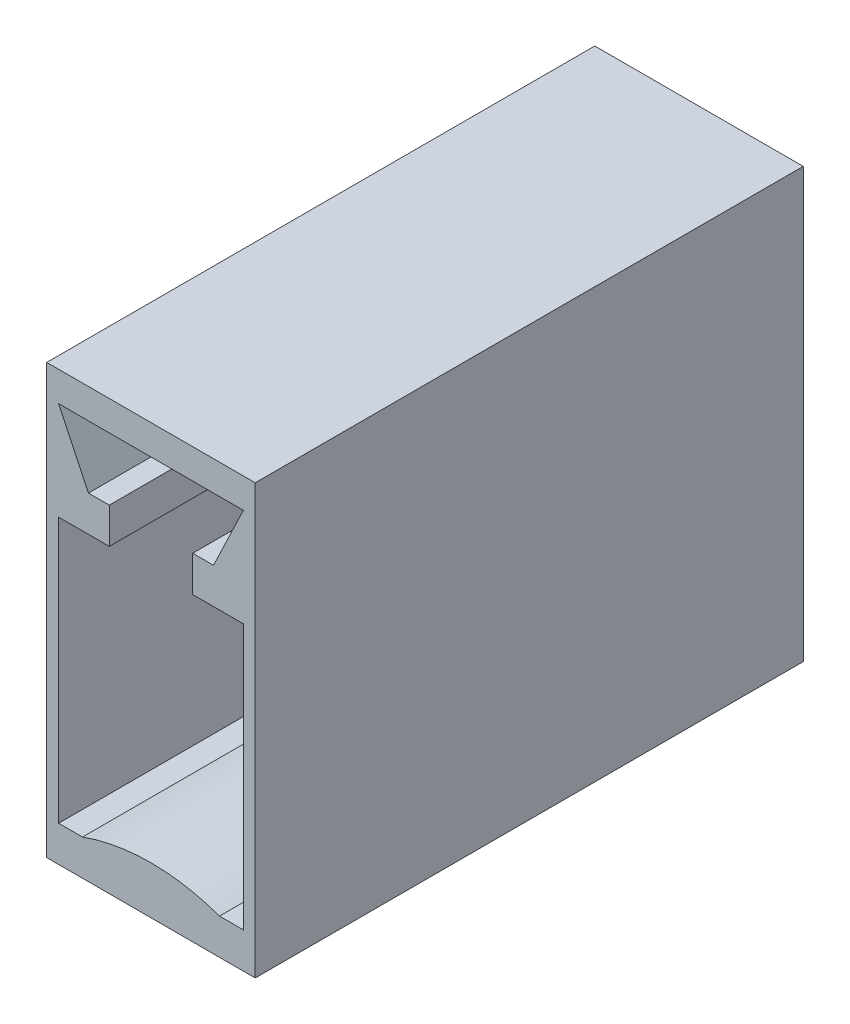
SolidWorks part; units mm, degrees
ref_plane "Спереди" through (0, 0, 0) normal (0, 0, 1) x (1, 0, 0)
ref_plane "Сверху" through (0, 0, 0) normal (0, 1, 0) x (1, 0, 0)
ref_plane "Справа" through (0, 0, 0) normal (1, 0, 0) x (0, 0, -1)
ref_plane "Плоскость1" through (0, -3.6, 0) normal (0, -1, 0) x (1, 0, 0)
sketch "Эскиз1" plane through (0, -3.6, 0) normal (0, -1, 0) x (1, 0, 0)
  line L0 (-3.5, 4.6) -> (-3.5, -4.6)
  line L1 (-3.5, -4.6) -> (0, -4.6)
  line L2 (0, -4.6) -> (0, 4.6)
  line L3 (0, 4.6) -> (-3.5, 4.6)
  line L4 (0, -3.9231) -> (0, 3.5325) construction
  dimension "D1" = 3.5
  dimension "D2" = 9.2
  dimension "D3" = 3.5
extrude "Бобышка-Вытянуть1" add sketch "Эскиз1" against normal blind 7.2
sketch "Эскиз2" plane through (0, -3.6, 0) normal (0, -1, 0) x (1, 0, 0)
  line L0 (-3.125, -1.55) -> (-3.125, -4.6)
  line L1 (-3.125, -4.6) -> (-0.375, -4.6)
  line L2 (-0.375, -4.6) -> (-0.375, -1.55)
  line L3 (-0.375, -1.55) -> (-3.125, -1.55)
extrude "Вырез-Вытянуть1" cut sketch "Эскиз2" against normal blind 0.4
sketch "Эскиз5" plane through (0, 0, -4.6) normal (0, 0, -1) x (-1, 0, 0)
  line L0 (0.375, 0.6) -> (0.375, -3.2)
  line L1 (0.375, -3.2) -> (3.125, -3.2)
  line L2 (3.125, -3.2) -> (3.125, 0.6)
  line L3 (3.125, 0.6) -> (0.375, 0.6)
extrude "Вырез-Вытянуть4" cut sketch "Эскиз5" against normal blind 0.4
ref_plane "Плоскость2" through (0, 0, -2.3) normal (0, 0, -1) x (-1, 0, 0)
sketch "Эскиз7" plane through (0, 0, -2.3) normal (0, 0, -1) x (-1, 0, 0)
  line L0 (3.3, -1.1) -> (3.3, -0.1)
  line L1 (3.3, -0.1) -> (2.9, -0.1)
  line L2 (2.9, -0.1) -> (2.9, 1.1)
  line L3 (2.9, 1.1) -> (0.6, 1.1)
  line L4 (0.6, 1.1) -> (0.6, -0.1)
  line L5 (0.6, -0.1) -> (0.2, -0.1)
  line L6 (0.2, -0.1) -> (0.2, -1.1)
  line L7 (0.2, -1.1) -> (0.6, -1.1)
  line L8 (0.6, -1.1) -> (0.6, -3)
  line L9 (2.9, -3) -> (2.9, -1.1)
  line L10 (2.9, -1.1) -> (3.3, -1.1)
  arc A0 (0.6, -3) -> (2.9, -3) centre (1.75, -6.2062) cw
extrude "Вырез-Вытянуть6" cut sketch "Эскиз7" against normal up to next
ref_plane "Плоскость3" through (0, 0, -1) normal (0, 0, 1) x (1, 0, 0)
sketch "Эскиз9" plane through (0, 0, -1) normal (0, 0, 1) x (1, 0, 0)
  circle A0 centre (-1.75, -0.6) radius 0.9
extrude "Бобышка-Вытянуть3" add sketch "Эскиз9" against normal up to surface (1.3 mm away) up to face at (-1.75, -0.7, -2.3)
sketch "Эскиз10" plane through (0, 0, -4.2) normal (0, 0, -1) x (-1, 0, 0)
  line L0 (1.35, -3.2) -> (2.15, -3.2)
  line L1 (2.15, -3.2) -> (2.15, -0.2)
  line L2 (2.15, -0.2) -> (1.35, -0.2)
  line L3 (1.35, -0.2) -> (1.35, -3.2)
extrude "Вырез-Вытянуть7" cut sketch "Эскиз10" against normal blind 1.2
ref_plane "Плоскость4" through (0, -0.2, 0) normal (0, 1, 0) x (1, 0, 0)
sketch "Эскиз11" plane through (0, -0.2, 0) normal (0, 1, 0) x (1, 0, 0)
  line L0 (-1.35, 3) -> (-2.15, 3)
  line L1 (-2.15, 3) -> (-2.15, 1)
  line L2 (-2.15, 1) -> (-1.35, 1)
  line L3 (-1.35, 1) -> (-1.35, 3)
extrude "Вырез-Вытянуть8" cut sketch "Эскиз11" against normal blind 0.8
fillet "Скругление2" radius 0.2 1 edges at (-2.65, -0.6, -1)
ref_plane "Плоскость5" through (0, 0, -3.4) normal (0, 0, -1) x (-1, 0, 0)
sketch "Эскиз15" plane through (0, 0, -3.4) normal (0, 0, -1) x (-1, 0, 0)
  line L0 (1.05, 2.05) -> (1.05, 1.45)
  line L1 (1.05, 1.45) -> (0.2, 1.45)
  line L2 (0.2, 1.45) -> (0.2, -0.1)
  line L3 (0.2, -0.1) -> (0.6, -0.1)
  line L4 (0.6, -0.1) -> (0.6, 1.1)
  line L5 (0.6, 1.1) -> (2.9, 1.1)
  line L6 (2.9, 1.1) -> (2.9, -0.1)
  line L7 (2.9, -0.1) -> (3.3, -0.1)
  line L8 (3.3, -0.1) -> (3.3, 1.45)
  line L9 (3.3, 1.45) -> (2.45, 1.45)
  line L10 (2.45, 1.45) -> (2.45, 2.05)
  line L11 (2.45, 2.05) -> (3.3, 2.05)
  line L12 (3.3, 2.05) -> (3.3, 3.1)
  line L13 (3.3, 3.1) -> (0.2, 3.1)
  line L14 (0.2, 3.1) -> (0.2, 2.05)
  line L15 (0.2, 2.05) -> (1.05, 2.05)
extrude "Вырез-Вытянуть12" cut sketch "Эскиз15" against normal up to next
draft "Уклон3" type of draft neutral plane draft angle 25.463 faces to draft 1 face at (-0.2, 2.575, 0.6) neutral plane through (-3.3, 3.1, 4.601) neutral plane normal (0, -1, 0) reverse direction yes parameters "D1"=25.463
draft "Уклон4" type of draft neutral plane draft angle 25.463 faces to draft 1 face at (-3.3, 2.575, 0.6) neutral plane through (-3.3, 3.1, 4.601) neutral plane normal (0, -1, 0) reverse direction yes parameters "D1"=25.463
sketch "Эскиз18" plane through (0, 0, -3.4) normal (0, 0, -1) x (-1, 0, 0)
  line L0 (0.2, -3) -> (0.6, -3)
  line L1 (0.6, -3) -> (0.6, -1.1)
  line L2 (0.6, -1.1) -> (0.2, -1.1)
  line L3 (0.2, -1.1) -> (0.2, -3)
extrude "Вырез-Вытянуть15" cut sketch "Эскиз18" against normal up to next
sketch "Эскиз19" plane through (0, 0, -3.4) normal (0, 0, -1) x (-1, 0, 0)
  line L0 (3.3, -3) -> (3.3, -1.1)
  line L1 (3.3, -1.1) -> (2.9, -1.1)
  line L2 (2.9, -1.1) -> (2.9, -3)
  line L3 (2.9, -3) -> (3.3, -3)
extrude "Вырез-Вытянуть16" cut sketch "Эскиз19" against normal up to next
